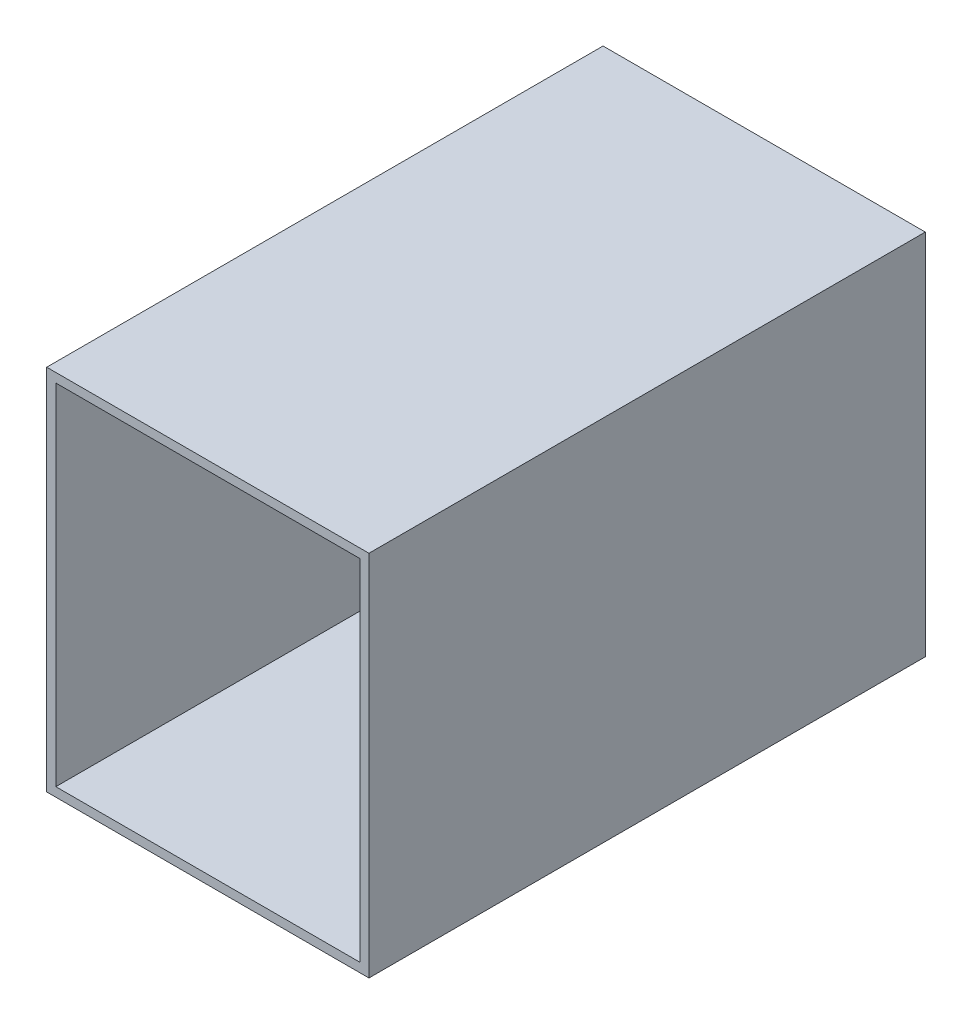
SolidWorks part; units mm, degrees
ref_plane "前视基准面" through (0, 0, 0) normal (0, 0, 1) x (1, 0, 0)
ref_plane "上视基准面" through (0, 0, 0) normal (0, 1, 0) x (1, 0, 0)
ref_plane "右视基准面" through (0, 0, 0) normal (1, 0, 0) x (0, 0, -1)
other "Configuration Table"
sketch "草图1" plane through (0, 0, 0) normal (0, 0, 1) x (1, 0, 0)
  line L0 (0, 0) -> (106, 0)
  line L1 (106, 0) -> (106, 121)
  line L2 (106, 121) -> (0, 121)
  line L3 (0, 121) -> (0, 0)
  dimension "width" = 106
  dimension "height" = 121
extrude "BlockExtrude" add sketch "草图1" along normal blind 183
shell "抽壳1" thickness 3
